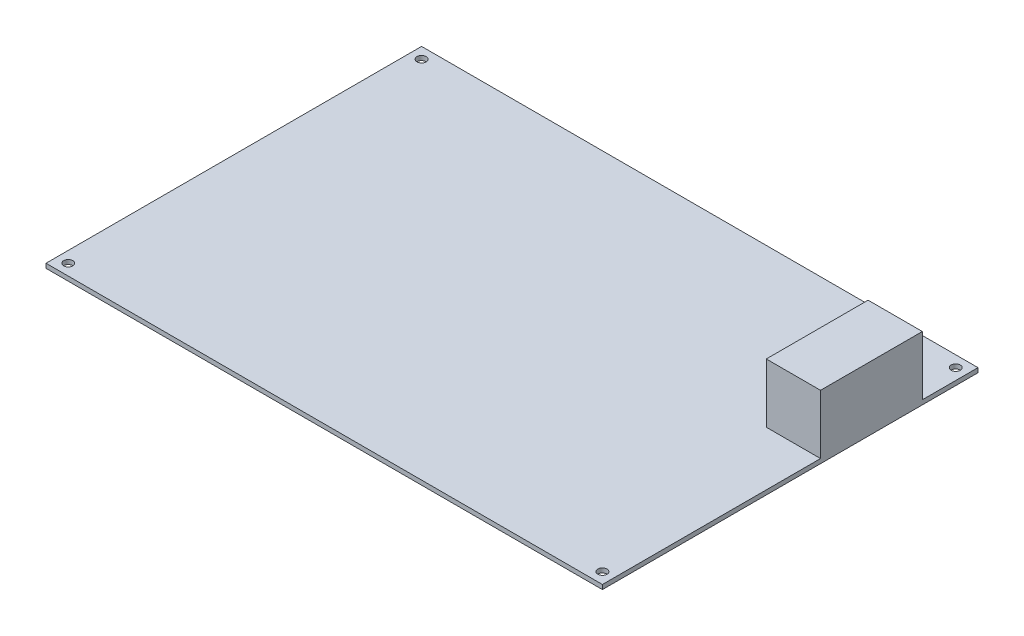
SolidWorks part; units mm, degrees
ref_plane "Front Plane" through (0, 0, 0) normal (0, 0, 1) x (1, 0, 0)
ref_plane "Top Plane" through (0, 0, 0) normal (0, 1, 0) x (1, 0, 0)
ref_plane "Right Plane" through (0, 0, 0) normal (1, 0, 0) x (0, 0, -1)
sketch "Sketch1" plane through (0, 0, 0) normal (0, 1, 0) x (1, 0, 0)
  line L0 (200, 67.5) -> (-82.8609, 67.5) construction
  line L1 (0, 0) -> (200, 0)
  line L2 (0, 0) -> (0, 135)
  line L3 (0, 135) -> (200, 135)
  line L4 (200, 0) -> (200, 135)
  line L5 (100, 135) -> (100, -15.7384) construction
  circle A0 centre (196, 131) radius 1.65
  circle A1 centre (4, 131) radius 1.65
  circle A2 centre (4, 4) radius 1.65
  circle A3 centre (196, 4) radius 1.65
  dimension "D3" = 3.3
  dimension "D1" = 135
  dimension "D2" = 200
  dimension "D4" = 4
  dimension "D5" = 4
extrude "Boss-Extrude1" add sketch "Sketch1" along normal blind 1.6
sketch "Sketch2" plane through (200, 0, 0) normal (1, 0, 0) x (0, 0, -1)
  line L1 (115, 1.6) -> (78.4, 1.6)
  line L2 (115, 1.6) -> (115, 22.85)
  line L3 (115, 22.85) -> (78.4, 22.85)
  line L4 (78.4, 1.6) -> (78.4, 22.85)
  line L10 (0, 1.6) -> (135, 1.6) construction
  dimension "D1" = 20
  dimension "D3" = 21.25
  dimension "D5" = 36.6
extrude "Boss-Extrude2" add sketch "Sketch2" against normal blind 19.5
